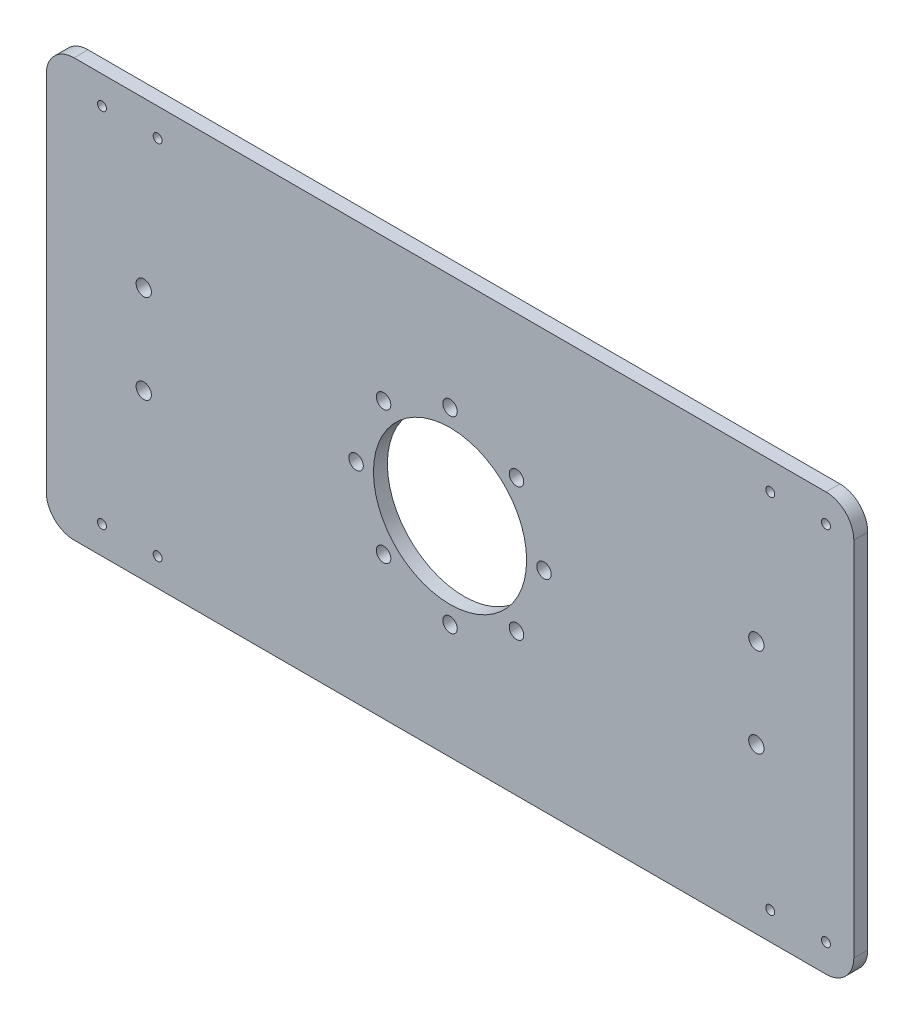
SolidWorks part; units mm, degrees
material "Thornel Mat VMA"
ref_plane "前视基准面" through (0, 0, 0) normal (0, 0, 1) x (1, 0, 0)
ref_plane "上视基准面" through (0, 0, 0) normal (0, 1, 0) x (1, 0, 0)
ref_plane "右视基准面" through (0, 0, 0) normal (1, 0, 0) x (0, 0, -1)
other "Configuration Table"
sketch "草图1" plane through (0, 0, 0) normal (0, 0, 1) x (1, 0, 0)
  line L1 (-145, 75) -> (145, 75)
  line L2 (-145, 75) -> (-145, -75)
  line L3 (-145, -75) -> (145, -75)
  line L4 (145, 75) -> (145, -75)
  line L5 (-145, 75) -> (145, -75) construction
  line L6 (-145, -75) -> (145, 75) construction
  point P0 (0, 0)
  dimension "D1" = 150
  dimension "D2" = 290
extrude "凸台-拉伸1" add sketch "草图1" along normal blind 5
sketch "草图5" plane through (0, 0, 0) normal (0, 0, -1) x (-1, 0, 0)
  circle A1 centre (0, 0) radius 27.5
  circle A2 centre (0, 0) radius 27.5
  circle A3 centre (23.8649, 23.8649) radius 2.6
  circle A4 centre (23.8649, 23.8649) radius 2.6
  circle A5 centre (0, 33.75) radius 2.6
  circle A6 centre (0, 33.75) radius 2.6
  circle A7 centre (-23.8649, 23.8649) radius 2.6
  circle A8 centre (-23.8649, 23.8649) radius 2.6
  circle A9 centre (-33.75, 0) radius 2.6
  circle A10 centre (-33.75, 0) radius 2.6
  circle A11 centre (-23.8649, -23.8649) radius 2.6
  circle A12 centre (-23.8649, -23.8649) radius 2.6
  circle A13 centre (0, -33.75) radius 2.6
  circle A14 centre (0, -33.75) radius 2.6
  circle A15 centre (23.8649, -23.8649) radius 2.6
  circle A16 centre (23.8649, -23.8649) radius 2.6
  circle A17 centre (33.75, 0) radius 2.6
  circle A18 centre (33.75, 0) radius 2.6
  dimension "D1" = 0
  dimension "D2" = 0
  dimension "D3" = 0
  dimension "D4" = 0
  dimension "D5" = 0
  dimension "D6" = 0
  dimension "D7" = 0
  dimension "D8" = 0
  dimension "D9" = 0
extrude "切除-拉伸2" cut sketch "草图5" against normal up to next
fillet "圆角1" radius 10 4 edges at (145, 75, 2.5) (145, -75, 2.5) (-145, -75, 2.5) (-145, 75, 2.5)
sketch "草图6" plane through (0, 0, 0) normal (0, 0, -1) x (-1, 0, 0)
  line L0 (135, -75) -> (-135, -75) construction
  line L1 (145, 65) -> (145, -65) construction
  circle A0 centre (110, -16) radius 2.75
  circle A1 centre (-110, -16) radius 2.75
  circle A2 centre (-110, 16) radius 2.75
  circle A3 centre (110, 16) radius 2.75
  dimension "D1" = 5.5
  dimension "D2" = 59
  dimension "D3" = 35
  dimension "D4" = 2
  dimension "D5" = 2
extrude "切除-拉伸3" cut sketch "草图6" against normal blind 10
sketch "草图7" plane through (0, 0, 0) normal (0, 0, -1) x (-1, 0, 0)
  line L0 (-135, 75) -> (135, 75) construction
  line L1 (-145, -65) -> (-145, 65) construction
  circle A0 centre (-135, 65) radius 1.6
  circle A1 centre (-115, 65) radius 1.6
  circle A2 centre (105, 65) radius 1.6
  circle A3 centre (125, 65) radius 1.6
  circle A4 centre (105, -65) radius 1.6
  circle A5 centre (125, -65) radius 1.6
  circle A6 centre (-135, -65) radius 1.6
  circle A7 centre (-115, -65) radius 1.6
  dimension "D1" = 3.2
  dimension "D2" = 3.2
  dimension "D3" = 10
  dimension "D4" = 10
  dimension "D5" = 10
  dimension "D6" = 20
  dimension "D7" = 2
  dimension "D8" = 2
extrude "切除-拉伸4" cut sketch "草图7" against normal blind 10
